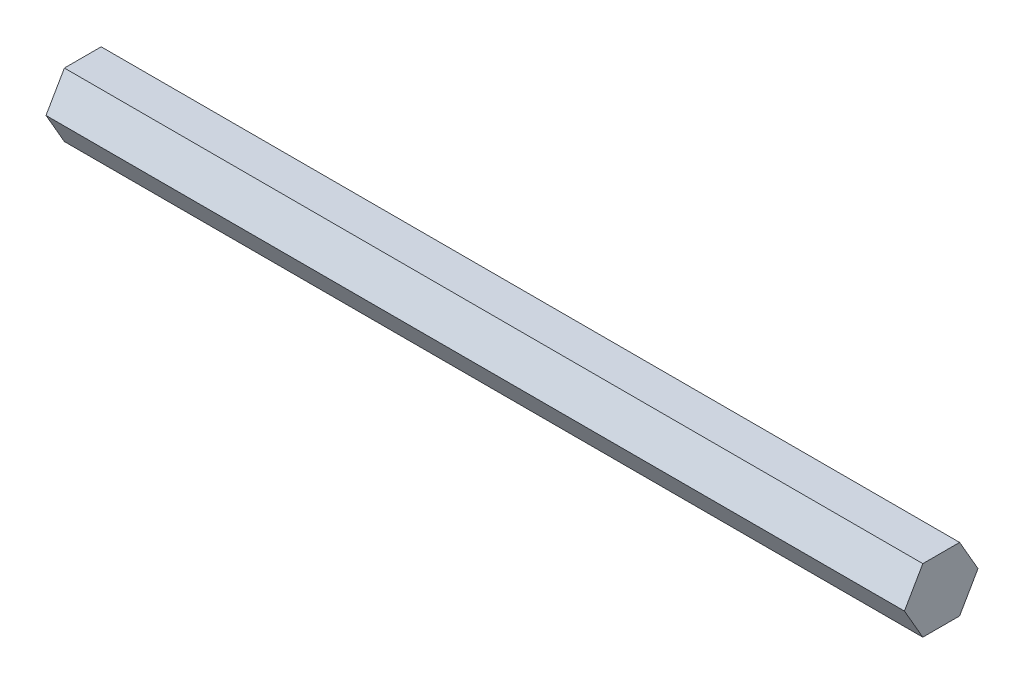
SolidWorks part; units mm, degrees
material "7075-T6 (SN)"
ref_plane "Front Plane" through (0, 0, 0) normal (0, 0, 1) x (1, 0, 0)
ref_plane "Top Plane" through (0, 0, 0) normal (0, 1, 0) x (1, 0, 0)
ref_plane "Right Plane" through (0, 0, 0) normal (1, 0, 0) x (0, 0, -1)
sketch "Sketch1" plane through (0, 0, 0) normal (1, 0, 0) x (0, 0, -1)
  line L1 (7.347, 0) -> (3.6735, 6.3627)
  line L2 (3.6735, 6.3627) -> (-3.6735, 6.3627)
  line L3 (-3.6735, 6.3627) -> (-7.347, 0)
  line L4 (-7.347, 0) -> (-3.6735, -6.3627)
  line L5 (-3.6735, -6.3627) -> (3.6735, -6.3627)
  line L6 (3.6735, -6.3627) -> (7.347, 0)
  circle A0 centre (0, 0) radius 6.3627 construction
  dimension "D1" = 12.7254
extrude "Boss-Extrude1" add sketch "Sketch1" along normal blind 171.45
move or copy body "Body-Move/Copy1" bodies to move or copy 103
